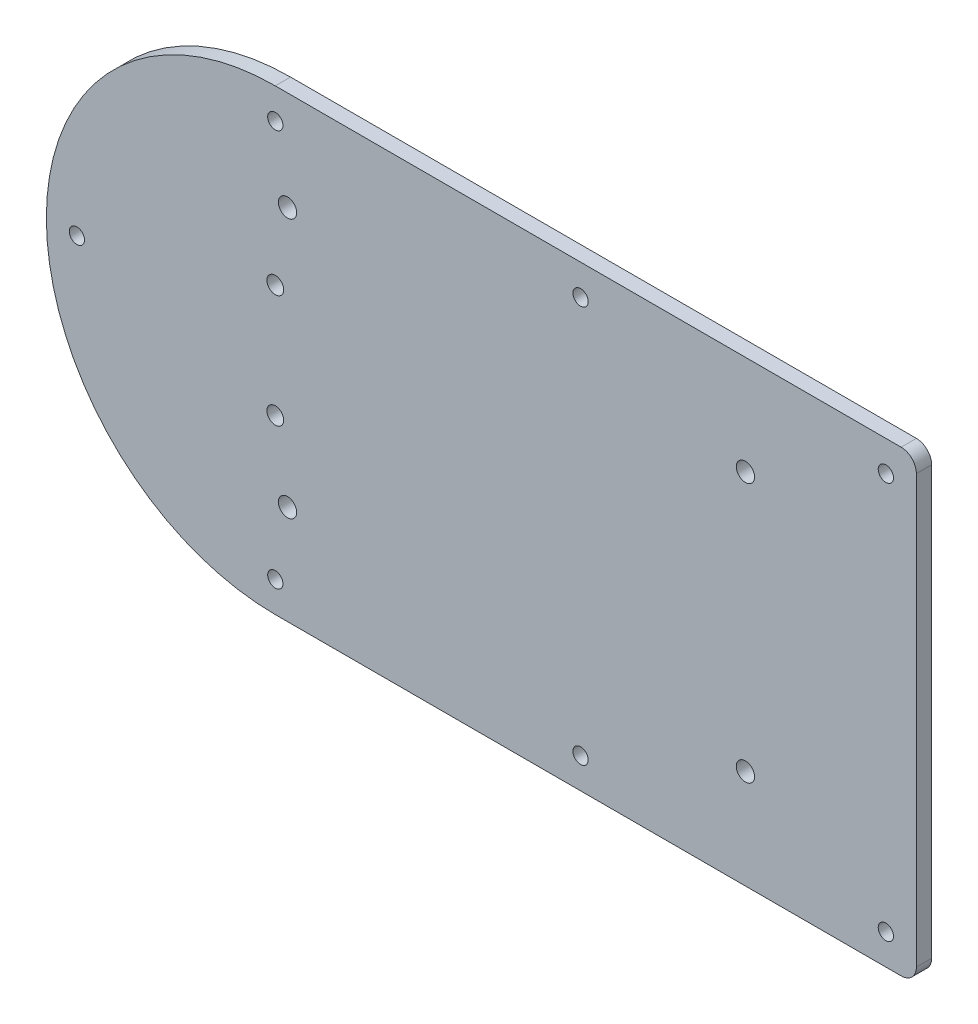
SolidWorks part; units mm, degrees
ref_plane "Front Plane" through (0, 0, 0) normal (0, 0, 1) x (1, 0, 0)
ref_plane "Top Plane" through (0, 0, 0) normal (0, 1, 0) x (1, 0, 0)
ref_plane "Right Plane" through (0, 0, 0) normal (1, 0, 0) x (0, 0, -1)
sketch "Sketch1" plane through (0, 0, 0) normal (0, 0, 1) x (1, 0, 0)
  line L1 (30.0007, 92.5455) -> (235.0007, 92.5455)
  line L3 (30.0007, -57.4545) -> (235.0007, -57.4545)
  line L4 (240.0007, 87.5455) -> (240.0007, -52.4545)
  arc A0 (235.0007, -57.4545) -> (240.0007, -52.4545) centre (235.0007, -52.4545) ccw
  arc A1 (235.0007, 92.5455) -> (240.0007, 87.5455) centre (235.0007, 87.5455) cw
  arc A2 (30.0007, 92.5455) -> (30.0007, -57.4545) centre (30.0007, 17.5455) ccw
  circle A3 centre (184.0007, 60.0455) radius 3
  circle A4 centre (184.0007, -24.9545) radius 3
  circle A5 centre (34.0007, 60.0455) radius 3
  circle A6 centre (34.0007, -24.9545) radius 3
  circle A7 centre (-34.9993, 17.5455) radius 2.5
  circle A8 centre (30.0007, 36.0455) radius 2.75
  circle A9 centre (30.0007, -0.9545) radius 2.75
  circle A10 centre (30.0007, -47.4545) radius 2.5
  circle A11 centre (30.0007, 82.5455) radius 2.5
  circle A12 centre (230.0007, -47.4545) radius 2.5
  circle A13 centre (230.0007, 82.5455) radius 2.5
  circle A15 centre (130.0007, 82.5455) radius 2.5
  circle A16 centre (130.0007, -47.4545) radius 2.5
  point P18 (34.0007, 60.0455)
  point P21 (-34.9993, 17.5455)
  dimension "D1" = 5
  dimension "D2" = 6
  dimension "D3" = 6
  dimension "D4" = 6
  dimension "D5" = 6
  dimension "D6" = 5
  dimension "D7" = 5.5
  dimension "D8" = 5.5
  dimension "D9" = 5
  dimension "D10" = 5
extrude "Boss-Extrude1" add sketch "Sketch1" along normal blind 5
